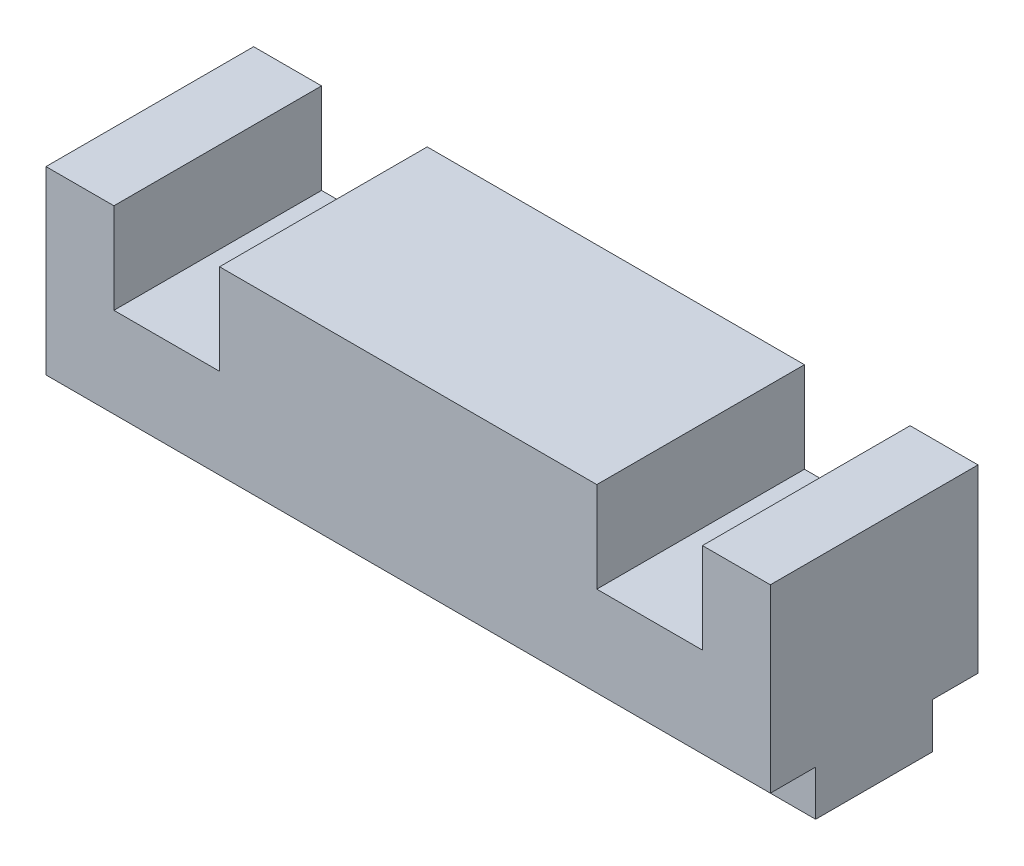
SolidWorks part; units mm, degrees
material "AISI 304"
ref_plane "Front Plane" through (0, 0, 0) normal (0, 0, 1) x (1, 0, 0)
ref_plane "Top Plane" through (0, 0, 0) normal (0, 1, 0) x (1, 0, 0)
ref_plane "Right Plane" through (0, 0, 0) normal (1, 0, 0) x (0, 0, -1)
sketch "Sketch1" plane through (0, 0, 0) normal (0, 1, 0) x (1, 0, 0)
  line L1 (-38.1, -10.922) -> (38.1, -10.922)
  line L2 (-38.1, -10.922) -> (-38.1, 10.922)
  line L3 (-38.1, 10.922) -> (38.1, 10.922)
  line L4 (38.1, -10.922) -> (38.1, 10.922)
  line L5 (-38.1, -10.922) -> (38.1, 10.922) construction
  line L6 (-38.1, 10.922) -> (38.1, -10.922) construction
  point P0 (0, 0)
  dimension "D1" = 76.2
  dimension "D2" = 21.844
extrude "Stock" add sketch "Sketch1" along normal blind 23.749
sketch "Bolt Hole Pattern" plane through (0, 23.749, 0) normal (0, 1, 0) x (1, 0, 0)
  point P0 (25.4, 0)
  point P1 (-25.4, 0)
  dimension "D1" = 25.4
  dimension "D2" = 25.4
hole_wizard "Clearance holes for Mounting Bolts " positions "Sketch4" profile "Sketch3" hole size "1/4" standard "ANSI Inch" end condition up to next
sketch "Sketch4" plane through (0, 23.749, 0) normal (0, 1, 0) x (1, 0, 0)
  point P0 (-25.4, 0)
  point P3 (25.4, 0)
sketch "Sketch3" plane through (-25.4, 23.749, 0) normal (1, 0, 0) x (0, 0, 1)
  line L0 (0, 0) -> (0, 23.749)
  line L1 (0, 23.749) -> (3.3782, 23.749)
  line L2 (3.3782, 23.749) -> (3.3782, 0)
  line L5 (3.3782, 0) -> (0, 0)
  line L11 (0, -6.35) -> (0, 107.95) construction
  dimension "Thru Hole Dia." = 6.7564
  dimension "Thru Hole Depth" = 23.749
sketch "Sketch5" plane through (0, 0, 0) normal (0, -1, 0) x (1, 0, 0)
  line L0 (38.1, 10.922) -> (38.1, -10.922) construction
  line L1 (-38.1, 10.922) -> (38.1, 10.922)
  line L2 (-38.1, 10.922) -> (-38.1, 6.1595)
  line L3 (-38.1, 6.1595) -> (38.1, 6.1595)
  line L4 (38.1, 10.922) -> (38.1, 6.1595)
  line L5 (-38.1, 0) -> (38.1, 0) construction
  line L6 (-38.1, -10.922) -> (-38.1, 10.922) construction
  line L7 (38.1, -10.922) -> (38.1, -6.1595)
  line L8 (-38.1, -6.1595) -> (38.1, -6.1595)
  line L9 (-38.1, -10.922) -> (-38.1, -6.1595)
  line L10 (-38.1, -10.922) -> (38.1, -10.922)
  dimension "D1" = 4.7625
extrude "Clearance Rabbit" cut sketch "Sketch5" against normal blind 4.7625
sketch "Sketch6" plane through (0, 0, 10.922) normal (0, 0, 1) x (1, 0, 0)
  line L0 (-38.1, 23.749) -> (38.1, 23.749) construction
  line L1 (-30.9562, 23.749) -> (-19.8438, 23.749)
  line L2 (-30.9562, 23.749) -> (-30.9562, 14.224)
  line L3 (-30.9562, 14.224) -> (-19.8437, 14.224)
  line L4 (-19.8438, 23.749) -> (-19.8437, 14.224)
  line L6 (30.9562, 23.749) -> (19.8437, 23.749)
  line L7 (30.9562, 23.749) -> (30.9562, 14.224)
  line L8 (30.9562, 14.224) -> (19.8438, 14.224)
  line L9 (19.8437, 23.749) -> (19.8438, 14.224)
  point P10 (-25.4, 14.224)
  point P12 (25.4, 14.224)
  dimension "D1" = 9.525
  dimension "D2" = 9.525
  dimension "D3" = 11.1125
  dimension "D4" = 11.1125
  dimension "D5" = 25.4
  dimension "D6" = 25.4
extrude "Cut-Extrude1" cut sketch "Sketch6" against normal through all
